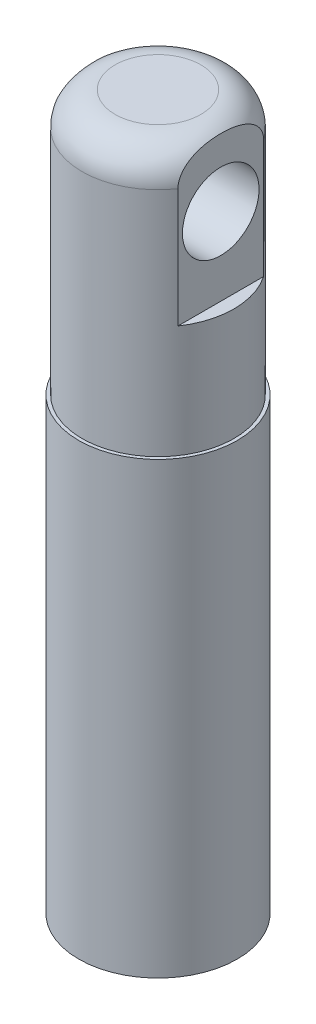
SolidWorks part; units mm, degrees
material "6061-T6 (SS)"
ref_plane "Front Plane" through (0, 0, 0) normal (0, 0, 1) x (1, 0, 0)
ref_plane "Top Plane" through (0, 0, 0) normal (0, 1, 0) x (1, 0, 0)
ref_plane "Right Plane" through (0, 0, 0) normal (1, 0, 0) x (0, 0, -1)
sketch "Sketch1" plane through (0, 0, 0) normal (0, 1, 0) x (1, 0, 0)
  circle A0 centre (0, 0) radius 11.5
  dimension "D1" = 23
extrude "Boss-Extrude1" add sketch "Sketch1" along normal blind 108
fillet "Fillet1" radius 5 1 edges at (0, 108, 11.5)
sketch "Sketch2" plane through (0, 0, 0) normal (0, -1, 0) x (1, 0, 0)
  circle A0 centre (0, 0) radius 9.5
  dimension "D1" = 19
extrude "Cut-Extrude1" cut sketch "Sketch2" against normal blind 80
cosmetic thread "Cosmetic Thread2" parameters "D2"=20
sketch "Sketch3" plane through (0, 108, 0) normal (0, 1, 0) x (1, 0, 0)
  line L0 (-9.5, 6.4807) -> (-9.5, -6.4807)
  line L1 (0, 11.5) -> (0, -11.5) construction
  line L2 (9.5, 6.4807) -> (9.5, -6.4807)
  circle A0 centre (0, 0) radius 11.5 construction
  arc A1 (-9.5, 6.4807) -> (-9.5, -6.4807) centre (0, 0) ccw
  arc A2 (9.5, -6.4807) -> (9.5, 6.4807) centre (0, 0) ccw
  dimension "D1" = 19
extrude "Cut-Extrude5" cut sketch "Sketch3" against normal blind 23
ref_plane "Plane1" through (0, 10, 0) normal (0, -1, 0) x (1, 0, 0)
sketch "Sketch6" plane through (0, 10, 0) normal (0, -1, 0) x (1, 0, 0)
  circle A0 centre (0, 0) radius 10.5
  dimension "D1" = 21
extrude "Cut-Extrude7" cut sketch "Sketch6" along normal blind 1
sketch "Sketch8" plane through (0, 0, 0) normal (0, -1, 0) x (1, 0, 0)
  circle A0 centre (0, 0) radius 12
  circle A1 centre (0, 0) radius 11.5 construction
  circle A2 centre (0, 0) radius 11.5
  dimension "D1" = 24
extrude "Boss-Extrude2" add sketch "Sketch8" against normal blind 68
cosmetic thread "Cosmetic Thread1" parameters "D1"=50, "D2"=21.797
sketch "Sketch9" plane through (-9.5, 0, 0) normal (-1, 0, 0) x (0, 0, 1)
  line L0 (6.5, 108) -> (-6.5, 108) construction
  circle A0 centre (0, 96.8) radius 5.8
  dimension "D1" = 11.6
  dimension "D2" = 11.2
extrude "Cut-Extrude8" cut sketch "Sketch9" against normal through all
